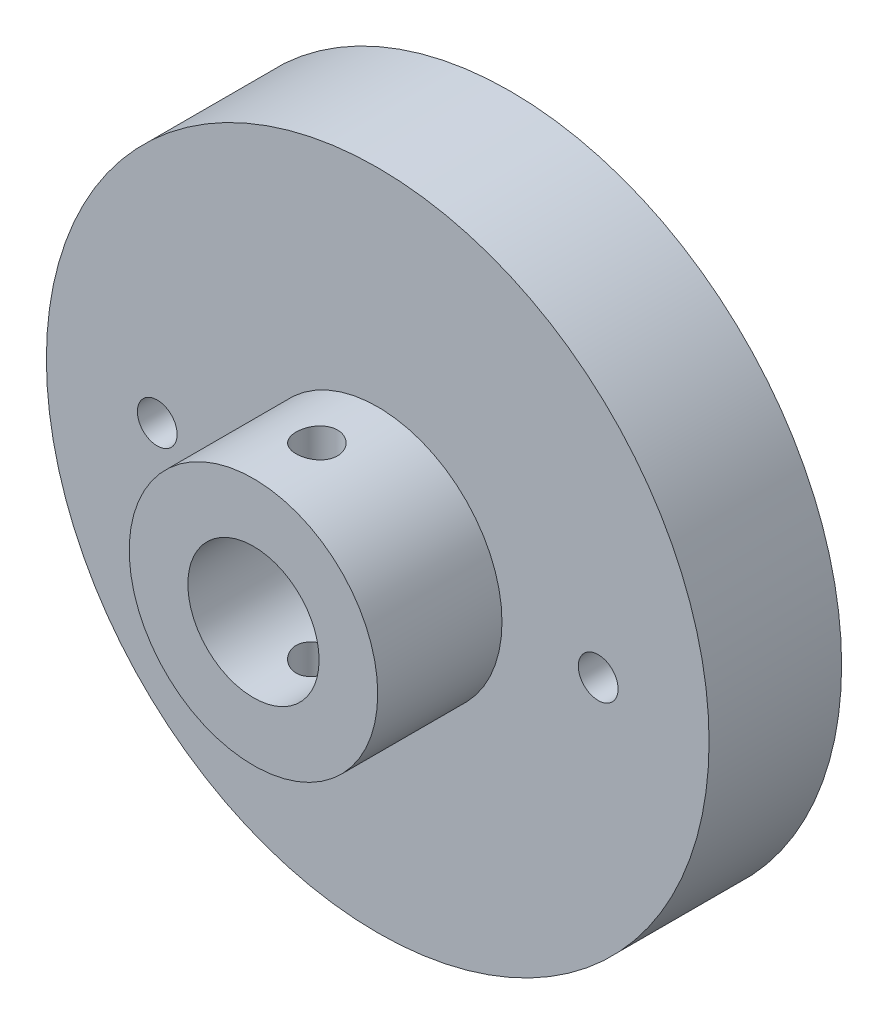
SolidWorks part; units mm, degrees
ref_plane "Front Plane" through (0, 0, 0) normal (0, 0, 1) x (1, 0, 0)
ref_plane "Top Plane" through (0, 0, 0) normal (0, 1, 0) x (1, 0, 0)
ref_plane "Right Plane" through (0, 0, 0) normal (1, 0, 0) x (0, 0, -1)
sketch "Sketch1" plane through (0, 0, 0) normal (0, 0, 1) x (1, 0, 0)
  circle A0 centre (0, 0) radius 12.7
  dimension "D1" = 25.4
extrude "Boss-Extrude1" add sketch "Sketch1" along normal blind 5.08
sketch "Sketch2" plane through (0, 0, 5.08) normal (0, 0, 1) x (1, 0, 0)
  circle A0 centre (-8.4506, 0) radius 0.762
  circle A1 centre (8.4506, 0) radius 0.762
  point P0 (-8.4506, 0)
  point P1 (8.4506, 0)
  dimension "D3" = 1.524
  dimension "D4" = 1.524
  dimension "D1" = 8.4506
  dimension "D2" = 8.4506
extrude "Cut-Extrude1" cut sketch "Sketch2" against normal through all
sketch "Sketch3" plane through (0, 0, 5.08) normal (0, 0, 1) x (1, 0, 0)
  circle A0 centre (0, 0) radius 4.7625
  dimension "D1" = 9.525
extrude "Boss-Extrude2" add sketch "Sketch3" along normal blind 4.7625
sketch "Sketch4" plane through (0, 0, 9.8425) normal (0, 0, 1) x (1, 0, 0)
  circle A0 centre (0, 0) radius 2.5146
  dimension "D1" = 5.0292
extrude "Cut-Extrude2" cut sketch "Sketch4" against normal through all
ref_plane "Plane1" through (0, 5.08, 0) normal (0, 1, 0) x (1, 0, 0)
sketch "Sketch5" plane through (0, 5.08, 0) normal (0, 1, 0) x (1, 0, 0)
  line L0 (-4.7625, -5.08) -> (4.7625, -5.08) construction
  line L2 (12.7, 0) -> (-12.7, 0) construction
  line L3 (-4.7625, -9.8425) -> (4.7625, -9.8425) construction
  line L5 (-4.7625, -5.08) -> (4.7625, -5.08) construction
  line L6 (-4.7625, -9.8425) -> (4.7625, -9.8425) construction
  line L8 (0, -14.605) -> (0, -5.08) construction
  line L9 (-4.7625, -7.4135) -> (4.7625, -7.4135) construction
  circle A0 centre (0, -7.4135) radius 0.7938
  point P0 (0, -7.4135)
  point P10 (0, -9.8425)
  dimension "D1" = 1.5875
  dimension "D2" = 0
extrude "Cut-Extrude3" cut sketch "Sketch5" against normal through all contours A0
